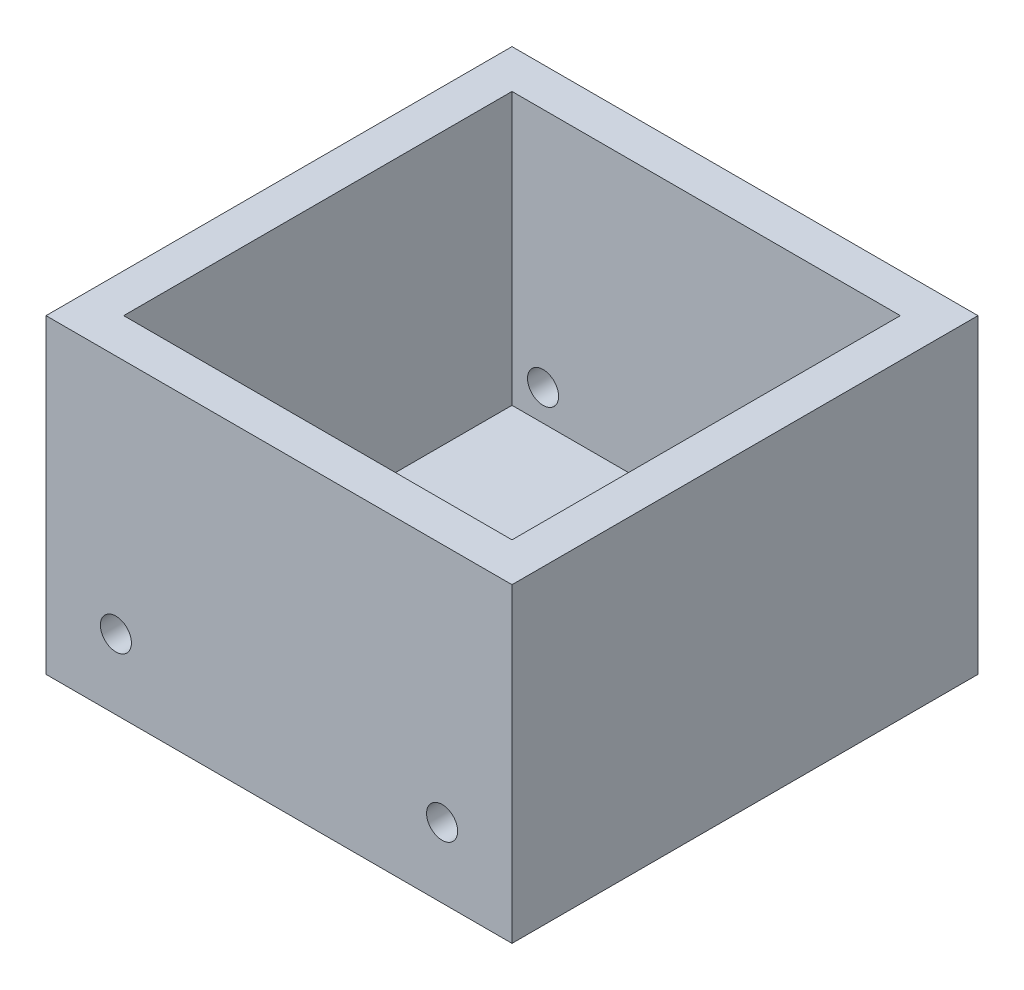
SolidWorks part; units mm, degrees
ref_plane "Front Plane" through (0, 0, 0) normal (0, 0, 1) x (1, 0, 0)
ref_plane "Top Plane" through (0, 0, 0) normal (0, 1, 0) x (1, 0, 0)
ref_plane "Right Plane" through (0, 0, 0) normal (1, 0, 0) x (0, 0, -1)
sketch "Sketch1" plane through (0, 0, 0) normal (0, 1, 0) x (1, 0, 0)
  line L1 (-76.2, -76.2) -> (76.2, -76.2)
  line L2 (-76.2, -76.2) -> (-76.2, 76.2)
  line L3 (-76.2, 76.2) -> (76.2, 76.2)
  line L4 (76.2, -76.2) -> (76.2, 76.2)
  line L5 (-76.2, -76.2) -> (76.2, 76.2) construction
  line L6 (-76.2, 76.2) -> (76.2, -76.2) construction
  point P0 (0, 0)
  dimension "D1" = 152.4
  dimension "D2" = 152.4
extrude "Boss-Extrude1" add sketch "Sketch1" along normal blind 101.6
shell "Shell1" thickness 12.7
sketch "Sketch2" plane through (0, 0, -63.5) normal (0, 0, 1) x (1, 0, 0)
  line L0 (-63.5, 101.6) -> (-63.5, 12.7) construction
  line L1 (63.5, 12.7) -> (-63.5, 12.7) construction
  line L2 (0, 86.07) -> (0, -25.2919) construction
  circle A0 centre (-53.34, 22.86) radius 5.08
  circle A1 centre (53.34, 22.86) radius 5.08
  dimension "D3" = 10.16
  dimension "D1" = 10.16
  dimension "D2" = 10.16
extrude "Cut-Extrude1" cut sketch "Sketch2" along normal through all
mirror "Mirror1" about plane through (0, 0, 0) normal (0, 0, 1) of "Cut-Extrude1"
